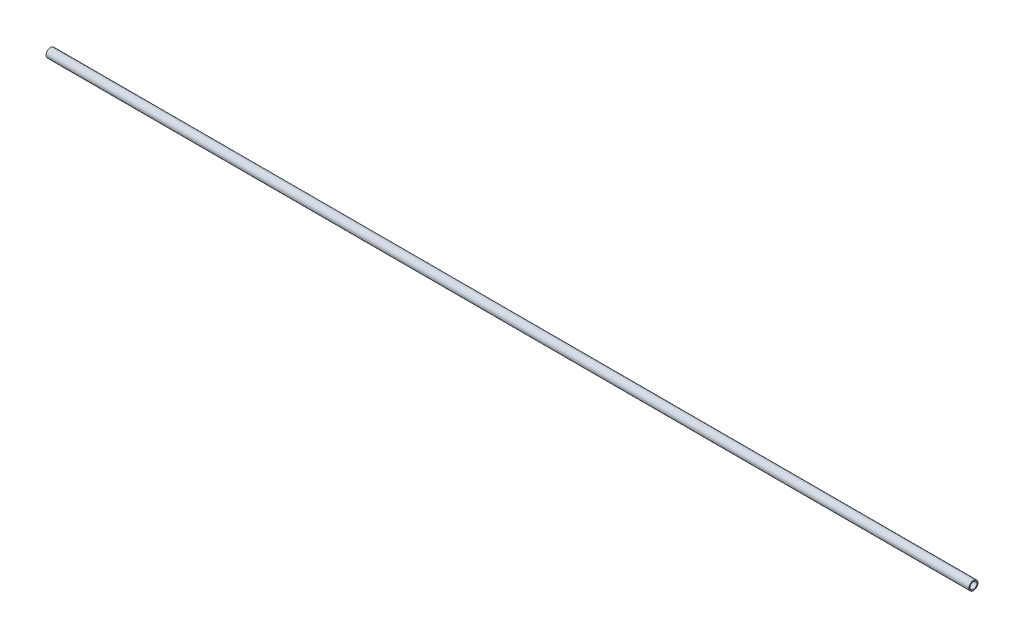
SolidWorks part; units mm, degrees
material "AISI 1010 Steel, hot rolled bar"
ref_plane "Front Plane" through (0, 0, 0) normal (0, 0, 1) x (1, 0, 0)
ref_plane "Top Plane" through (0, 0, 0) normal (0, 1, 0) x (1, 0, 0)
ref_plane "Right Plane" through (0, 0, 0) normal (1, 0, 0) x (0, 0, -1)
sketch "Sketch1" plane through (0, 0, 0) normal (1, 0, 0) x (0, 0, -1)
  circle A0 centre (0, 0) radius 12.7
  circle A1 centre (0, 0) radius 9.652
  dimension "D1" = 25.4
  dimension "D2" = 19.304
extrude "Boss-Extrude1" add sketch "Sketch1" along normal blind 2606.04
